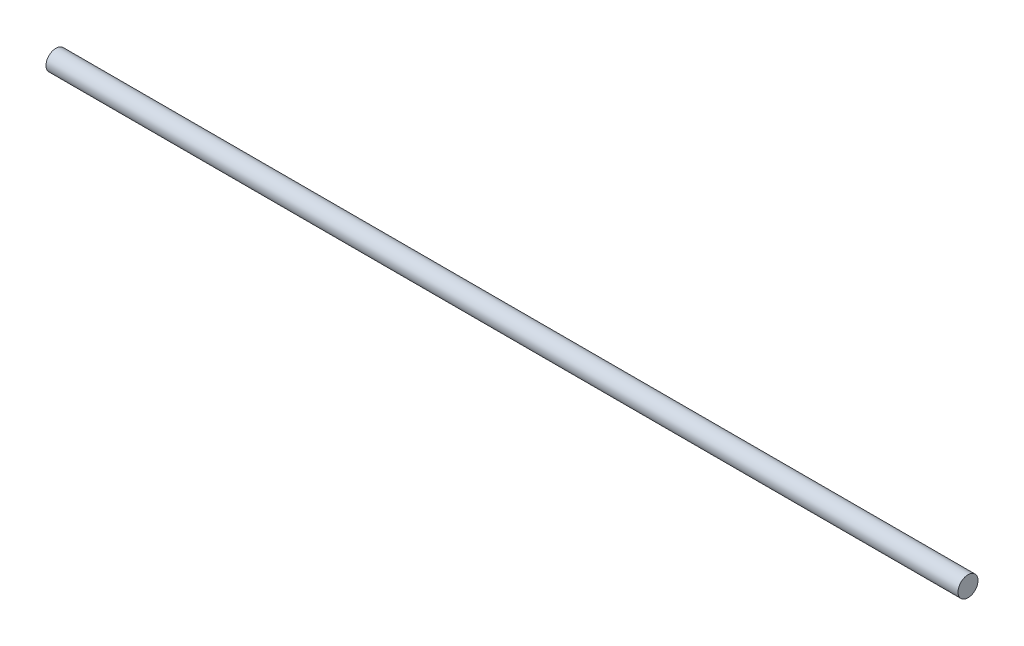
SolidWorks part; units mm, degrees
ref_plane "Alzado" through (0, 0, 0) normal (0, 0, 1) x (1, 0, 0)
ref_plane "Planta" through (0, 0, 0) normal (0, 1, 0) x (1, 0, 0)
ref_plane "Vista lateral" through (0, 0, 0) normal (1, 0, 0) x (0, 0, -1)
sketch "Croquis1" plane through (0, 0, 0) normal (1, 0, 0) x (0, 0, -1)
  circle A0 centre (0, 0) radius 2.5
  dimension "D1" = 5
extrude "Saliente-Extruir1" add sketch "Croquis1" along normal blind 228
